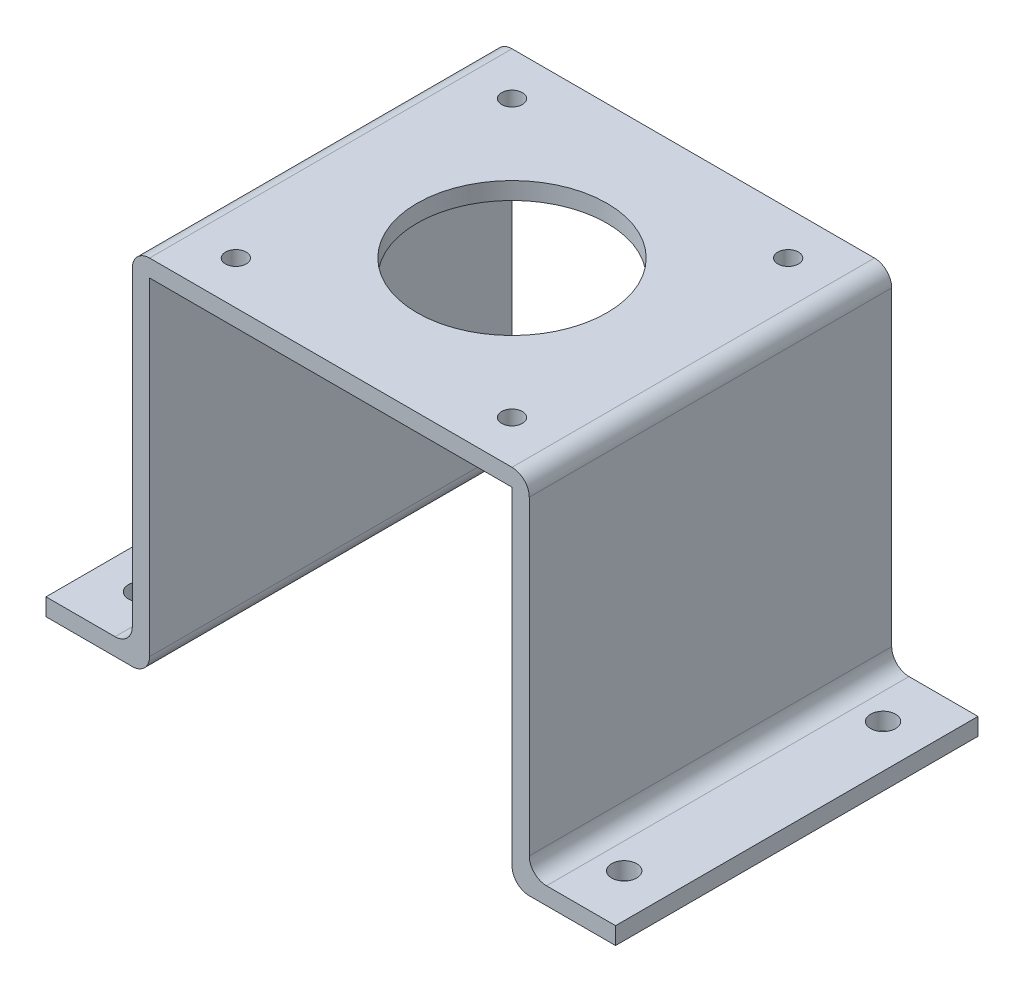
SolidWorks part; units mm, degrees
ref_plane "Plan de face" through (0, 0, 0) normal (0, 0, 1) x (1, 0, 0)
ref_plane "Plan de dessus" through (0, 0, 0) normal (0, 1, 0) x (1, 0, 0)
ref_plane "Plan de droite" through (0, 0, 0) normal (1, 0, 0) x (0, 0, -1)
sketch "Esquisse1" plane through (0, 0, 0) normal (0, 0, 1) x (1, 0, 0)
  line L0 (0, 0) -> (12, 0)
  line L1 (12, 0) -> (12, 40)
  line L2 (12, 40) -> (54, 40)
  line L3 (54, 40) -> (54, 0)
  line L4 (54, 0) -> (66, 0)
  line L5 (66, 0) -> (66, 2)
  line L6 (66, 2) -> (56, 2)
  line L7 (56, 2) -> (56, 42)
  line L8 (56, 42) -> (10, 42)
  line L9 (10, 42) -> (10, 2)
  line L10 (10, 2) -> (0, 2)
  line L11 (0, 2) -> (0, 0)
  dimension "D1" = 2
  dimension "D2" = 2
  dimension "D3" = 2
  dimension "D4" = 2
  dimension "D5" = 2
  dimension "D6" = 10
  dimension "D7" = 10
  dimension "D8" = 46
  dimension "D9" = 40
extrude "Boss.-Extru.1" add sketch "Esquisse1" along normal blind 42
sketch "Esquisse2" plane through (0, 2, 0) normal (0, 1, 0) x (1, 0, 0)
  line L0 (5, -6) -> (5, -36) construction
  line L2 (5, -6) -> (61, -6) construction
  line L4 (61, -6) -> (61, -36) construction
  line L6 (5, -36) -> (61, -36) construction
  line L7 (66, -42) -> (66, 0) construction
  point P0 (5, -6)
  point P2 (5, -36)
  point P4 (61, -6)
  point P6 (61, -36)
  dimension "D1" = 5
  dimension "D2" = 5
  dimension "D3" = 30
  dimension "D4" = 6
hole_wizard "Dégagement M2.51" positions "Esquisse2" profile "Esquisse3" hole size "M2.5" standard "ISO" end condition through all
sketch "Esquisse3" plane through (5, 2, 6) normal (1, 0, 0) x (0, 0, 1)
  line L0 (0, 0) -> (0, 2)
  line L1 (0, 2) -> (1.45, 2)
  line L2 (1.45, 2) -> (1.45, 0)
  line L5 (1.45, 0) -> (0, 0)
  line L11 (0, -6.35) -> (0, 107.95) construction
  dimension "Diamètre du perçage jusqu'au prochain" = 2.9
  dimension "Profondeur du perçage jusqu'au prochain" = 2
sketch "Esquisse4" plane through (0, 42, 0) normal (0, 1, 0) x (1, 0, 0)
  line L3 (56, -42) -> (10, -42) construction
  line L5 (17, -5) -> (17, -37) construction
  line L6 (17, -37) -> (49, -37) construction
  line L7 (49, -37) -> (49, -5) construction
  line L8 (49, -5) -> (17, -5) construction
  line L10 (56, -42) -> (56, 0) construction
  point P0 (17, -5)
  point P2 (49, -37)
  point P35 (17, -37)
  point P38 (49, -5)
  dimension "D1" = 32
  dimension "D2" = 32
  dimension "D3" = 5
  dimension "D4" = 7
hole_wizard "Dégagement M21" positions "Esquisse4" profile "Esquisse5" hole size "M2" standard "ISO" end condition through all
sketch "Esquisse5" plane through (17, 42, 5) normal (1, 0, 0) x (0, 0, 1)
  line L0 (0, 0) -> (0, 42)
  line L1 (0, 42) -> (1.2, 42)
  line L2 (1.2, 42) -> (1.2, 0)
  line L5 (1.2, 0) -> (0, 0)
  line L11 (0, -6.35) -> (0, 107.95) construction
  dimension "Diamètre du perçage jusqu'au prochain" = 2.4
  dimension "Profondeur du perçage jusqu'au prochain" = 42
sketch "Esquisse6" plane through (0, 42, 0) normal (0, 1, 0) x (1, 0, 0)
  line L0 (10, -42) -> (10, 0) construction
  line L1 (56, -42) -> (10, -42) construction
  circle A0 centre (33, -21) radius 11
  dimension "D1" = 22
  dimension "D2" = 23
  dimension "D3" = 21
extrude "Enlèv. mat.-Extru.1" cut sketch "Esquisse6" against normal up to next
fillet "Congé1" radius 2 6 edges at (12, 0, 21) (54, 0, 21) (56, 2, 21) (56, 42, 21) (10, 42, 21) (10, 2, 21)
